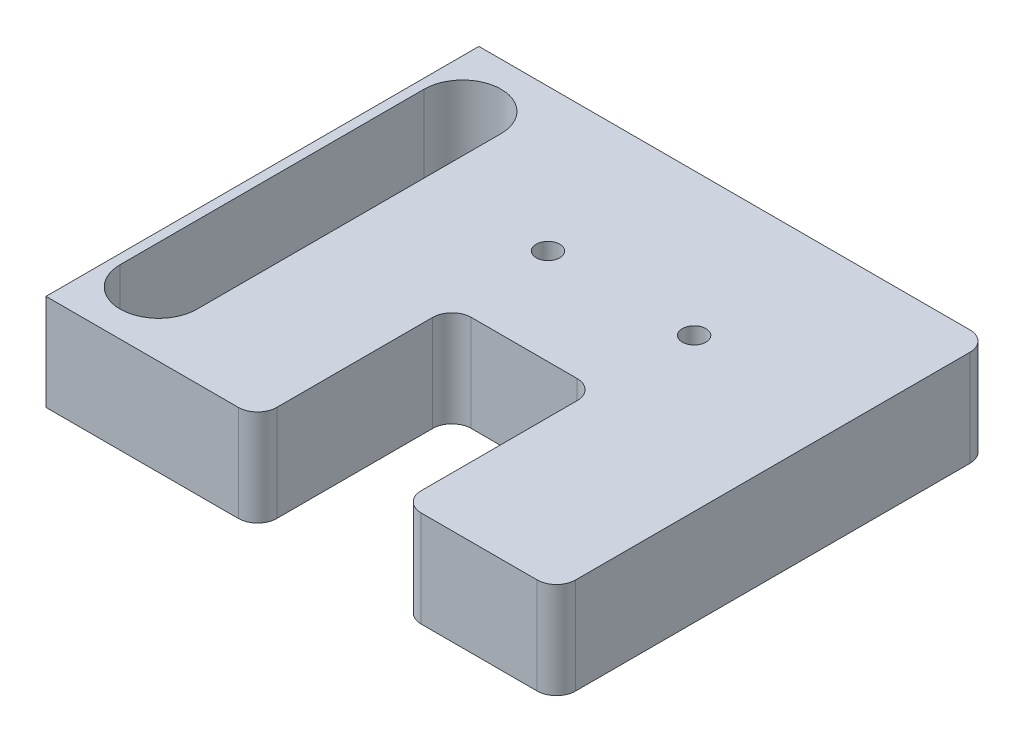
SolidWorks part; units mm, degrees
ref_plane "Front Plane" through (0, 0, 0) normal (0, 0, 1) x (1, 0, 0)
ref_plane "Top Plane" through (0, 0, 0) normal (0, 1, 0) x (1, 0, 0)
ref_plane "Right Plane" through (0, 0, 0) normal (1, 0, 0) x (0, 0, -1)
sketch "Sketch1" plane through (0, 0, 0) normal (0, 1, 0) x (1, 0, 0)
  line L8 (-28.9537, 0) -> (24.0763, 0)
  line L9 (24.0763, 0) -> (24.0763, -44.98)
  line L10 (24.0763, -44.98) -> (8.0263, -44.98)
  line L11 (8.0263, -44.98) -> (8.0263, -24.78)
  line L12 (8.0263, -24.78) -> (-6.9737, -24.78)
  line L13 (-6.9737, -24.78) -> (-6.9737, -44.98)
  line L14 (-6.9737, -44.98) -> (-28.9537, -44.98)
  line L15 (-28.9537, -44.98) -> (-28.9537, 0)
  dimension "D1" = 53.03
  dimension "D2" = 44.98
  dimension "D3" = 15
  dimension "D4" = 20.2
  dimension "D5" = 16.05
  dimension "D6" = 21.98
extrude "Boss-Extrude1" add sketch "Sketch1" along normal blind 10
sketch "Sketch2" plane through (0, 10, 0) normal (0, 1, 0) x (1, 0, 0)
  line L0 (-27.9537, -6.7) -> (-27.9537, -38.28)
  line L1 (-23.9537, -38.28) -> (-23.9537, -42.28) construction
  line L2 (-28.9537, -44.98) -> (-6.9737, -44.98) construction
  line L3 (-23.9537, -6.7) -> (-23.9537, -2.7) construction
  line L4 (24.0763, 0) -> (-28.9537, 0) construction
  line L5 (-23.9537, -38.28) -> (-27.9537, -38.28) construction
  line L6 (-19.9537, -6.7) -> (-19.9537, -38.28)
  line L7 (-28.9537, 0) -> (-28.9537, -44.98) construction
  line L8 (-23.9537, -6.7) -> (-27.9537, -6.7) construction
  line L9 (-27.9537, -6.7) -> (-19.9537, -6.7) construction
  arc A2 (-27.9537, -6.7) -> (-19.9537, -6.7) centre (-23.9537, -6.7) cw
  arc A3 (-27.9537, -38.28) -> (-19.9537, -38.28) centre (-23.9537, -38.28) ccw
  dimension "D2" = 2.7
  dimension "D4" = 2.7
  dimension "D5" = 1
  dimension "D6" = 1
fillet "Fillet1" radius 2 1 edges at (-6.9737, 5, 24.78)
fillet "Fillet2" radius 2 1 edges at (8.0263, 5, 24.78)
fillet "Fillet3" radius 2 1 edges at (-6.9737, 5, 44.98)
fillet "Fillet4" radius 2 1 edges at (8.0263, 5, 44.98)
fillet "Fillet5" radius 2 1 edges at (24.0763, 5, 0)
fillet "Fillet6" radius 2 1 edges at (24.0763, 5, 44.98)
sketch "Sketch4" plane through (0, 10, 0) normal (0, 1, 0) x (1, 0, 0)
  line L0 (22.0763, 0) -> (-28.9537, 0) construction
  line L1 (24.0763, -42.98) -> (24.0763, -2) construction
  line L3 (-28.9537, 0) -> (-28.9537, -44.98) construction
  circle A0 centre (-6.9587, -14.825) radius 1.225
  circle A1 centre (8.2313, -14.825) radius 1.225
  point P4 (-6.9587, -13.6)
  point P7 (8.2313, -13.6)
  point P8 (9.4563, -14.825)
  point P11 (-8.1837, -14.825)
  point P14 (-5.7337, -14.825)
  point P15 (7.0063, -14.825)
  dimension "D1" = 2.45
  dimension "D2" = 2.45
  dimension "D3" = 13.6
  dimension "D4" = 14.62
  dimension "D5" = 20.77
  dimension "D6" = 12.74
extrude "Cut-Extrude3" cut sketch "Sketch4" against normal through all and the other way through all
extrude "Cut-Extrude4" cut sketch "Sketch2" against normal blind 10
